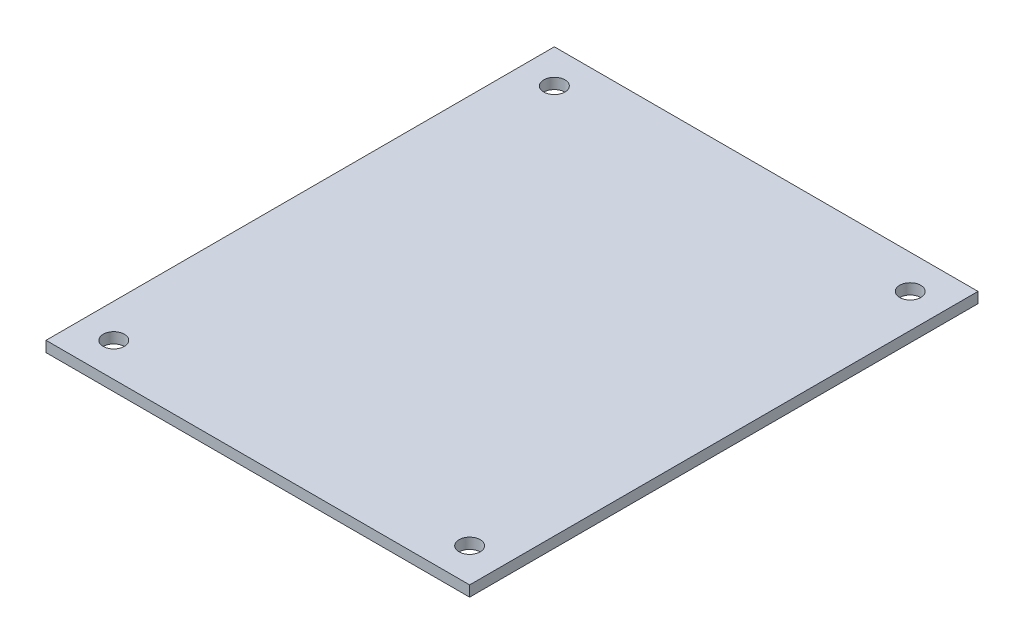
SolidWorks part; units mm, degrees
ref_plane "Front Plane" through (0, 0, 0) normal (0, 0, 1) x (1, 0, 0)
ref_plane "Top Plane" through (0, 0, 0) normal (0, 1, 0) x (1, 0, 0)
ref_plane "Right Plane" through (0, 0, 0) normal (1, 0, 0) x (0, 0, -1)
sketch "Sketch1" plane through (0, 0, 0) normal (0, 1, 0) x (1, 0, 0)
  line L0 (0, 76.2) -> (63.5, 0) construction
  line L1 (0, 0) -> (63.5, 0)
  line L2 (0, 0) -> (0, 76.2)
  line L3 (0, 76.2) -> (63.5, 76.2)
  line L4 (63.5, 0) -> (63.5, 76.2)
  line L5 (5.08, 5.08) -> (58.42, 71.12) construction
  circle A0 centre (5.08, 5.08) radius 1.5875
  circle A1 centre (58.42, 5.08) radius 1.5875
  circle A2 centre (58.42, 71.12) radius 1.5875
  circle A3 centre (5.08, 71.12) radius 1.5875
  point P7 (31.75, 38.1)
  dimension "D3" = 3.175
  dimension "D1" = 76.2
  dimension "D2" = 63.5
  dimension "D4" = 5.08
  dimension "D5" = 5.08
  dimension "D6" = 2
  dimension "D7" = 2
extrude "Boss-Extrude1" add sketch "Sketch1" along normal blind 1.6
